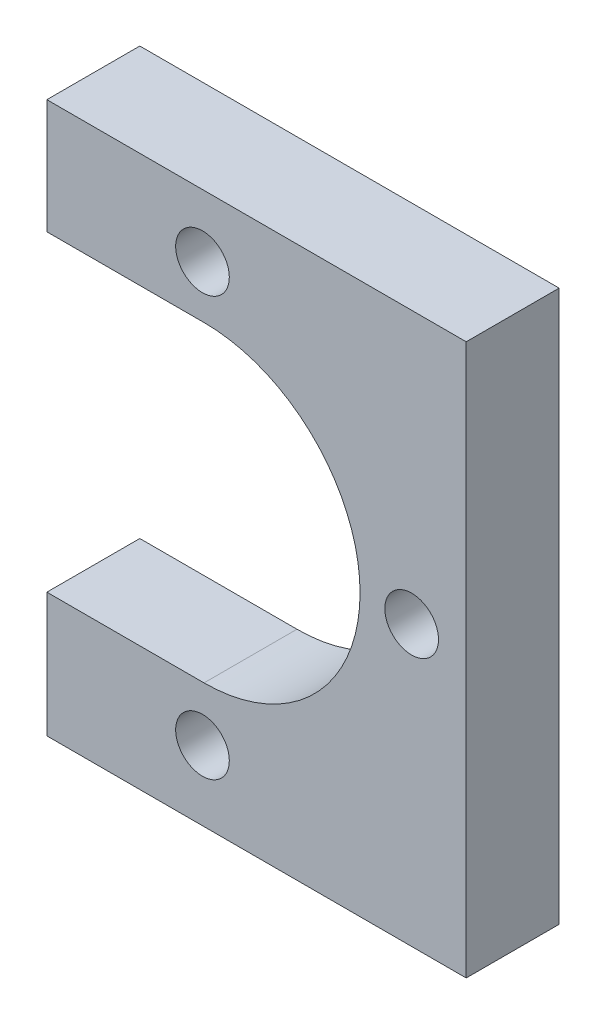
SolidWorks part; units mm, degrees
ref_plane "Alzado" through (0, 0, 0) normal (0, 0, 1) x (1, 0, 0)
ref_plane "Planta" through (0, 0, 0) normal (0, 1, 0) x (1, 0, 0)
ref_plane "Vista lateral" through (0, 0, 0) normal (1, 0, 0) x (0, 0, -1)
sketch "Croquis1" plane through (0, 0, 0) normal (0, 0, 1) x (1, 0, 0)
  line L0 (21.5, 28.25) -> (-21.5, -28.25) construction
  line L1 (-21.5, 28.25) -> (21.5, 28.25)
  line L2 (-21.5, 28.25) -> (-21.5, -28.25)
  line L3 (-21.5, -28.25) -> (21.5, -28.25)
  line L4 (21.5, 28.25) -> (21.5, -28.25)
  dimension "D1" = 56.5
  dimension "D2" = 43
extrude "Saliente-Extruir1" add sketch "Croquis1" along normal blind 9.53
sketch "Croquis2" plane through (0, 0, 9.53) normal (0, 0, 1) x (1, 0, 0)
  line L0 (-5.384, 28.25) -> (-5.384, 0.515) construction
  line L1 (21.5, 28.25) -> (-21.5, 28.25) construction
  line L2 (-5.384, 0.515) -> (21.5, 0.515) construction
  line L3 (21.5, -28.25) -> (21.5, 28.25) construction
  line L4 (-5.384, 16.515) -> (-21.5, 16.515)
  line L5 (-21.5, 28.25) -> (-21.5, -28.25) construction
  line L6 (-21.5, 16.515) -> (-24.0158, 16.515)
  line L7 (-5.384, -15.485) -> (-21.5, -15.485)
  line L8 (-24.0158, 16.515) -> (-24.0158, -15.485)
  line L9 (-24.0158, -15.485) -> (-21.5, -15.485)
  line L10 (-21.5, -15.485) -> (-21.7721, -15.6227)
  arc A0 (-5.384, -15.485) -> (-5.384, 16.515) centre (-5.384, 0.515) ccw
  line M1 (-21.5, 28.25) -> (-21.5, -28.25)
  dimension "D3" = 32
  dimension "D1" = 26.884
  dimension "D2" = 27.735
extrude "Cortar-Extruir1" cut sketch "Croquis2" against normal blind 9.53 contours L7 A0 L4 M1
sketch "Croquis3" plane through (0, 0, 9.53) normal (0, 0, 1) x (1, 0, 0)
  line L0 (21.5, -28.25) -> (21.5, 28.25) construction
  line L1 (21.5, 28.25) -> (-21.5, 28.25) construction
  line L2 (-21.5, -28.25) -> (21.5, -28.25) construction
  circle A0 centre (15.908, 0.383) radius 2.75
  circle A1 centre (-5.542, 21.833) radius 2.75
  circle A2 centre (-5.542, -21.105) radius 2.75
  dimension "D1" = 5.5
  dimension "D4" = 5.5
  dimension "D5" = 5.5
  dimension "D2" = 5.592
  dimension "D3" = 27.867
  dimension "D6" = 6.417
  dimension "D7" = 7.145
  dimension "D8" = 27.042
  dimension "D9" = 27.042
extrude "Cortar-Extruir2" cut sketch "Croquis3" against normal up to next
